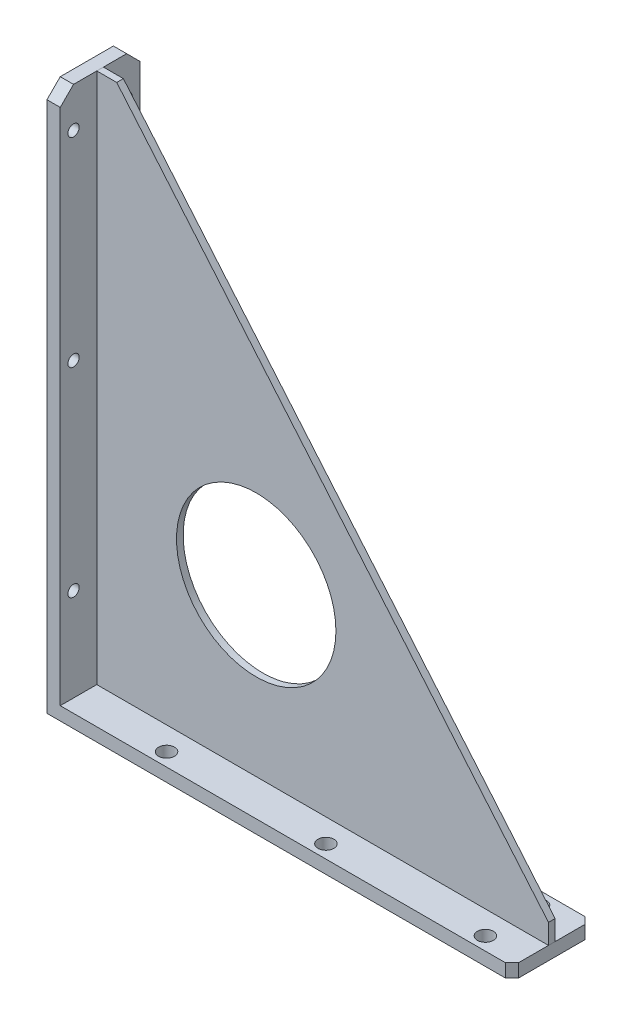
SolidWorks part; units mm, degrees
material "Q235"
ref_plane "前视基准面" through (0, 0, 0) normal (0, 0, 1) x (1, 0, 0)
ref_plane "上视基准面" through (0, 0, 0) normal (0, 1, 0) x (1, 0, 0)
ref_plane "右视基准面" through (0, 0, 0) normal (1, 0, 0) x (0, 0, -1)
sketch "草图1" plane through (0, 0, 0) normal (0, 0, 1) x (1, 0, 0)
  line L0 (0, 0) -> (0, 410)
  line L1 (0, 410) -> (10, 410)
  line L2 (10, 410) -> (10, 10)
  line L3 (10, 10) -> (350, 10)
  line L4 (350, 10) -> (350, 0)
  line L5 (350, 0) -> (0, 0)
  point P3 (5, 410)
  dimension "D1" = 10
  dimension "D2" = 10
  dimension "D3" = 350
  dimension "D4" = 400
extrude "凸台-拉伸1" add sketch "草图1" along normal blind 60
chamfer "倒角1" distance 10 angle 45 2 edges at (5, 410, 60) (5, 410, 0)
chamfer "倒角2" distance 5 angle 45 2 edges at (350, 5, 0) (350, 5, 60)
other "角撑板1" parameters "D1"=5, "D2"=5, "D3"=0, "D4"=0, "D10"=5, "D11"=400, "D12"=340, "D13"=15, "D14"=49.83, "D15"=15, "D16"=50, "D17"=25, "D18"=26.565
sketch "草图6" plane through (10, 10, 30) normal (0, 0, -1) x (-1, 0, 0)
  line L0 (0, 0) -> (0, 400)
  line L1 (0, 0) -> (-340, 0)
  line L2 (-15, 400) -> (-340, 15)
  line L3 (0, 400) -> (-15, 400)
  line L4 (-340, 0) -> (-340, 15)
hole_wizard "M10 螺纹孔2" positions "草图7" profile "草图8" tap size "M10" standard "GB"
sketch "草图7" plane through (10, 0, 0) normal (1, 0, 0) x (0, 0, -1)
  line L0 (0, 10) -> (0, 400) construction
  line L1 (-50, 410) -> (-10, 410) construction
  point P0 (-50, 380)
  point P2 (-50, 230)
  point P4 (-10, 380)
  point P6 (-10, 230)
  point P14 (-50, 80)
  point P16 (-10, 80)
  point P19 (0, 0)
  point P20 (0, 0)
  dimension "D1" = 40
  dimension "D2" = 10
  dimension "D3" = 30
  dimension "D4" = 150
  dimension "D5" = 150
sketch "草图8" plane through (10, 380, 50) normal (0, 1, 0) x (0, 0, -1)
  line L0 (0, 0) -> (0, 30.0537)
  line L1 (0, 30.0537) -> (4.25, 27.5)
  line L2 (4.25, 27.5) -> (4.25, 0)
  line L5 (4.25, 0) -> (0, 0)
  line L10 (0, 30.0537) -> (-4.25, 27.5) construction
  line L11 (0, -6.35) -> (0, 107.95) construction
  dimension "螺纹孔钻头直径" = 8.5
  dimension "螺纹孔钻头深度" = 27.5
  dimension "导头角度" = 118
hole_wizard "Ø12.0 (12) 直径孔3" positions "草图9" profile "草图10" hole size "Ø12.0" standard "GB"
sketch "草图9" plane through (0, 10, 0) normal (0, 1, 0) x (1, 0, 0)
  line L0 (345, -60) -> (10, -60) construction
  line L4 (350, -55) -> (350, -5) construction
  point P0 (200, -50)
  point P2 (320, -50)
  point P4 (200, -10)
  point P11 (320, -10)
  point P19 (80, -50)
  point P21 (80, -10)
  dimension "D1" = 10
  dimension "D2" = 40
  dimension "D3" = 30
  dimension "D4" = 120
  dimension "D5" = 120
sketch "草图10" plane through (200, 10, 50) normal (1, 0, 0) x (0, 0, 1)
  line L0 (0, 0) -> (0, 31.1052)
  line L1 (0, 31.1052) -> (6, 27.5)
  line L2 (6, 27.5) -> (6, 0)
  line L5 (6, 0) -> (0, 0)
  line L10 (0, 31.1052) -> (-6, 27.5) construction
  line L11 (0, -6.35) -> (0, 107.95) construction
  dimension "孔直径" = 12
  dimension "孔深度" = 27.5
  dimension "导头角度" = 118
sketch "草图11" plane through (0, 0, 32.5) normal (0, 0, 1) x (1, 0, 0)
  line L0 (345, 10) -> (10, 10) construction
  line L1 (10, 10) -> (10, 400) construction
  circle A0 centre (130, 135) radius 60
  dimension "D1" = 120
  dimension "D2" = 125
  dimension "D3" = 120
extrude "切除-拉伸1" cut sketch "草图11" against normal blind 10 contours A0
